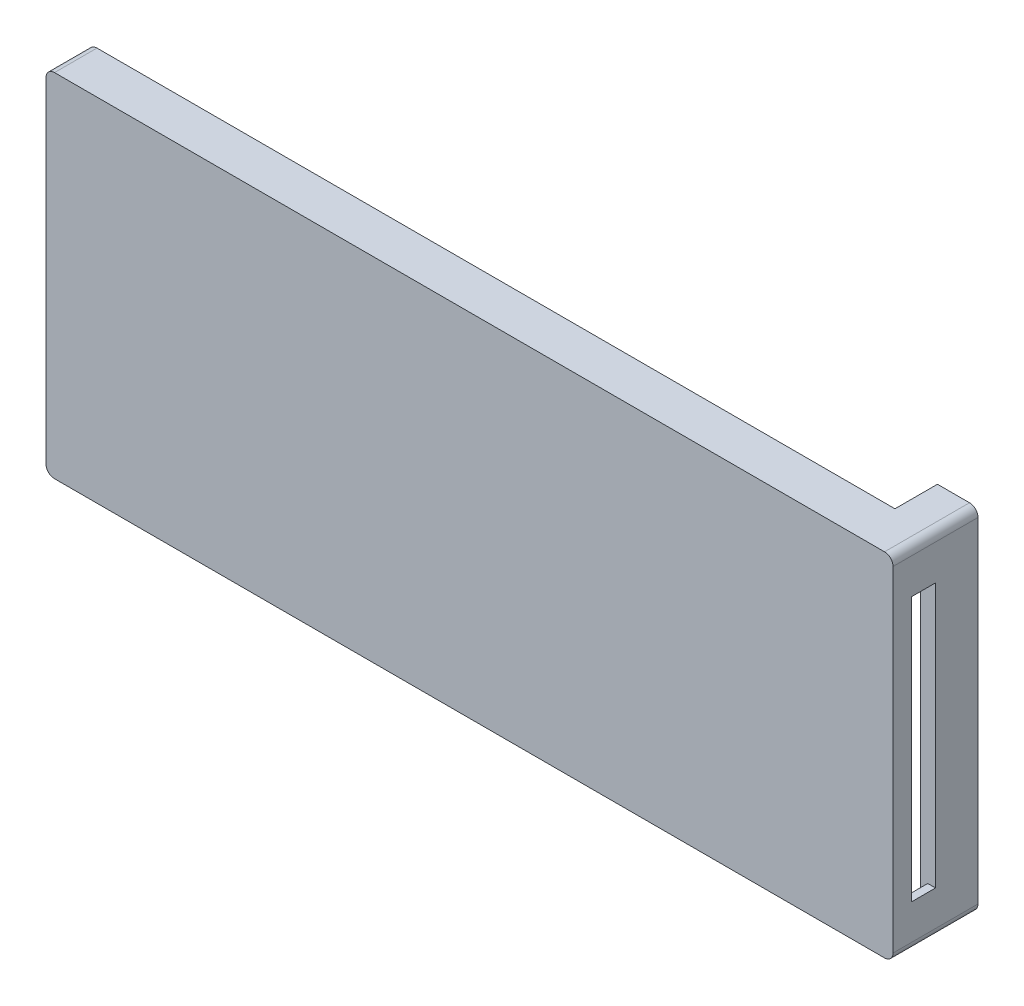
SolidWorks part; units mm, degrees
ref_plane "Plan de face" through (0, 0, 0) normal (0, 0, 1) x (1, 0, 0)
ref_plane "Plan de dessus" through (0, 0, 0) normal (0, 1, 0) x (1, 0, 0)
ref_plane "Plan de droite" through (0, 0, 0) normal (1, 0, 0) x (0, 0, -1)
sketch "Esquisse1" plane through (0, 0, 0) normal (0, 0, 1) x (1, 0, 0)
  line L1 (0, 0) -> (199.3831, 0)
  line L2 (0, 0) -> (0, 82.7933)
  line L3 (0, 82.7933) -> (199.3831, 82.7933)
  line L4 (199.3831, 0) -> (199.3831, 82.7933)
extrude "Boss.-Extru.1" add sketch "Esquisse1" along normal blind 10
sketch "Esquisse2" plane through (0, 0, 0) normal (0, 0, -1) x (-1, 0, 0)
  line L0 (0, 0) -> (-199.3831, 0) construction
  line L1 (-199.3831, 82.7933) -> (-189.8364, 82.7933)
  line L2 (-199.3831, 82.7933) -> (-199.3831, 0)
  line L3 (-199.3831, 0) -> (-189.8364, 0)
  line L4 (-189.8364, 82.7933) -> (-189.8364, 0)
extrude "Boss.-Extru.3" add sketch "Esquisse2" along normal blind 10
sketch "Esquisse3" plane through (189.8364, 0, 0) normal (-1, 0, 0) x (0, 0, 1)
  line L0 (0, 0) -> (0, 82.7933) construction
  line L1 (0, 1.0986) -> (-7.5223, 1.0986)
  line L2 (0, 1.0986) -> (0, 81.3365)
  line L3 (0, 81.3365) -> (-7.5223, 81.3365)
  line L4 (-7.5223, 1.0986) -> (-7.5223, 81.3365)
extrude "Enlèv. mat.-Extru.1" cut sketch "Esquisse3" against normal blind 6
sketch "Esquisse4" plane through (0, 0, 0) normal (0, 0, -1) x (-1, 0, 0)
  line L1 (-197.5514, 81.3365) -> (-2.6802, 81.3365)
  line L2 (-197.5514, 81.3365) -> (-197.5514, 3.418)
  line L3 (-197.5514, 3.418) -> (-2.6802, 3.418)
  line L4 (-2.6802, 81.3365) -> (-2.6802, 3.418)
extrude "Enlèv. mat.-Extru.2" cut sketch "Esquisse4" against normal blind 6
sketch "Esquisse5" plane through (199.3831, 0, 0) normal (1, 0, 0) x (0, 0, -1)
  line L1 (0, 72.4625) -> (-5.6559, 72.4625)
  line L2 (0, 72.4625) -> (0, 10.2647)
  line L3 (0, 10.2647) -> (-5.6559, 10.2647)
  line L4 (-5.6559, 72.4625) -> (-5.6559, 10.2647)
extrude "Enlèv. mat.-Extru.3" cut sketch "Esquisse5" against normal blind 6
fillet "Congé1" radius 2 1 edges at (199.3831, 0, 0)
fillet "Congé2" radius 2 1 edges at (199.3831, 82.7933, 0)
fillet "Congé3" radius 2 1 edges at (0, 82.7933, 5)
fillet "Congé4" radius 2 1 edges at (0, 0, 5)
